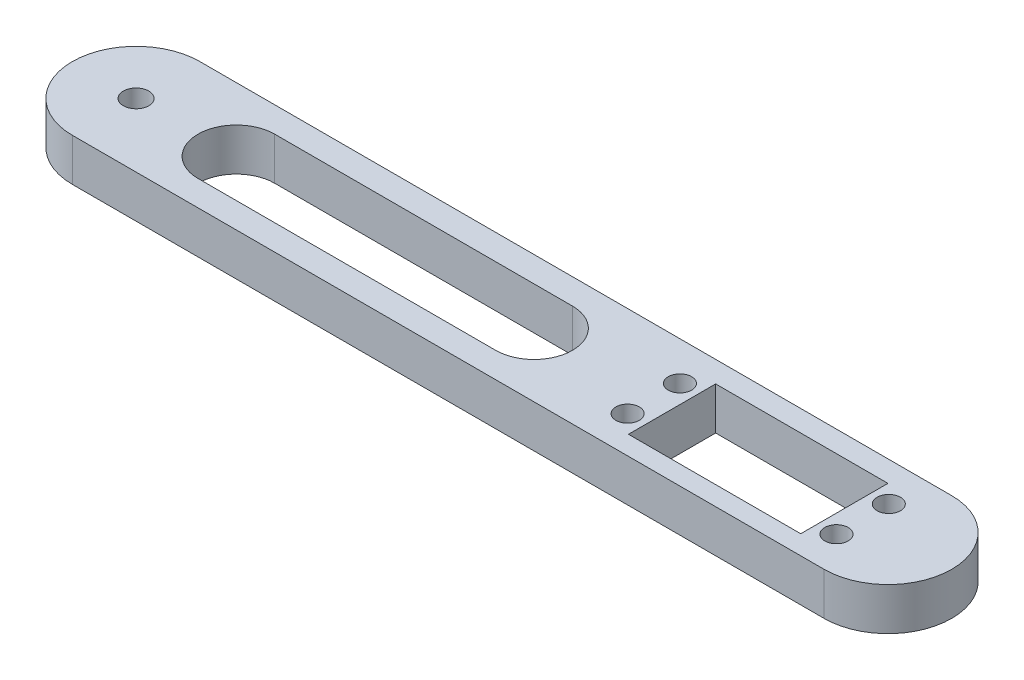
SolidWorks part; units mm, degrees
ref_plane "Front Plane" through (0, 0, 0) normal (0, 0, 1) x (1, 0, 0)
ref_plane "Top Plane" through (0, 0, 0) normal (0, 1, 0) x (1, 0, 0)
ref_plane "Right Plane" through (0, 0, 0) normal (1, 0, 0) x (0, 0, -1)
sketch "Sketch2" plane through (0, 0, 0) normal (0, 1, 0) x (1, 0, 0)
  line L0 (0, 0) -> (100, 0) construction
  line L1 (0, 15) -> (100, 15)
  line L2 (0, -15) -> (100, -15)
  arc A0 (0, 15) -> (0, -15) centre (0, 0) ccw
  arc A1 (100, -15) -> (100, 15) centre (100, 0) ccw
  circle A2 centre (0, 0) radius 1.45
  point P3 (50, 0)
  dimension "D1" = 15
  dimension "D3" = 2.9
  dimension "D2" = 100
extrude "Boss-Extrude3" add sketch "Sketch2" along normal blind 10
sketch "Sketch6" plane through (0, 10, 0) normal (0, 1, 0) x (1, 0, 0)
  line L0 (100, 15) -> (0, 15) construction
  line L1 (49.5013, 10) -> (90.0013, 10)
  line L2 (49.5013, 10) -> (49.5013, -10.5)
  line L3 (49.5013, -10.5) -> (90.0013, -10.5)
  line L4 (90.0013, 10) -> (90.0013, -10.5)
  arc A0 (100, -15) -> (100, 15) centre (100, 0) ccw construction
  circle A1 centre (94.3013, 5.9) radius 2.75
  circle A2 centre (94.3013, -6.4) radius 2.75
  point P9 (90.0013, -0.25)
  point P10 (115, 0)
  dimension "D1" = 5.5
  dimension "D5" = 4.3
  dimension "0.42" = 5.5
  dimension "D2" = 40.5
  dimension "D3" = 5
  dimension "D4" = 25
  dimension "D6" = 4.3
  dimension "D7" = 4.1
  dimension "D8" = 4.1
  dimension "D9" = 20.5
sketch "Sketch10" plane through (0, 10, 0) normal (0, 1, 0) x (1, 0, 0)
  line L1 (91.2578, 10.7582) -> (98.305, 10.7582)
  line L2 (91.2578, 10.7582) -> (91.2578, -9.1019)
  line L3 (91.2578, -9.1019) -> (98.305, -9.1019)
  line L4 (98.305, 10.7582) -> (98.305, -9.1019)
extrude "Boss-Extrude7" add sketch "Sketch10" against normal blind 10
sketch "Sketch12" plane through (0, 10, 0) normal (0, 1, 0) x (1, 0, 0)
  line L0 (-76.7564, 0) -> (12.1761, 0) construction
  line L1 (-76.7564, 15) -> (12.1761, 15)
  line L2 (-76.7564, -15) -> (12.1761, -15)
  arc A0 (-76.7564, 15) -> (-76.7564, -15) centre (-76.7564, 0) ccw
  arc A1 (12.1761, -15) -> (12.1761, 15) centre (12.1761, 0) ccw
  circle A2 centre (-76.7564, 0) radius 1.45
  point P3 (-32.2901, 0)
  dimension "D1" = 2.9
  dimension "D2" = 15
extrude "Boss-Extrude8" add sketch "Sketch12" against normal blind 10
sketch "Sketch13" plane through (0, 10, 0) normal (0, 1, 0) x (1, 0, 0)
  circle A0 centre (-76.7564, 0) radius 2.925
  dimension "D1" = 5.85
extrude "Cut-Extrude8" cut sketch "Sketch13" against normal blind 2
sketch "Sketch15" plane through (0, 10, 0) normal (0, 1, 0) x (1, 0, 0)
  line L0 (-53.1809, 0) -> (16.8191, 0) construction
  line L1 (-53.1809, 9.0182) -> (16.8191, 9.0182)
  line L2 (-53.1809, -9.0182) -> (16.8191, -9.0182)
  arc A0 (-53.1809, 9.0182) -> (-53.1809, -9.0182) centre (-53.1809, 0) ccw
  arc A1 (16.8191, -9.0182) -> (16.8191, 9.0182) centre (16.8191, 0) ccw
  point P3 (-18.1809, 0)
  dimension "D1" = 70
extrude "Cut-Extrude9" cut sketch "Sketch15" against normal blind 10
sketch "Sketch16" plane through (0, 10, 0) normal (0, 1, 0) x (1, 0, 0)
  circle A0 centre (-76.7564, 0) radius 3
  dimension "D1" = 6
extrude "Cut-Extrude10" cut sketch "Sketch16" against normal blind 10
extrude "Cut-Extrude11" cut sketch "Sketch6" against normal blind 10
sketch "Sketch17" plane through (0, 10, 0) normal (0, 1, 0) x (1, 0, 0)
  line L0 (49.5013, 10) -> (49.5013, -10.5) construction
  circle A0 centre (45.2013, 5.9) radius 2.75
  circle A1 centre (45.2013, -6.4) radius 2.75
  dimension "D1" = 5.5
  dimension "0.55" = 5.5
  dimension "D4" = 4.3
  dimension "D2" = 4.3
  dimension "D3" = 4.1
  dimension "D5" = 4.1
extrude "Cut-Extrude12" cut sketch "Sketch17" against normal blind 10
